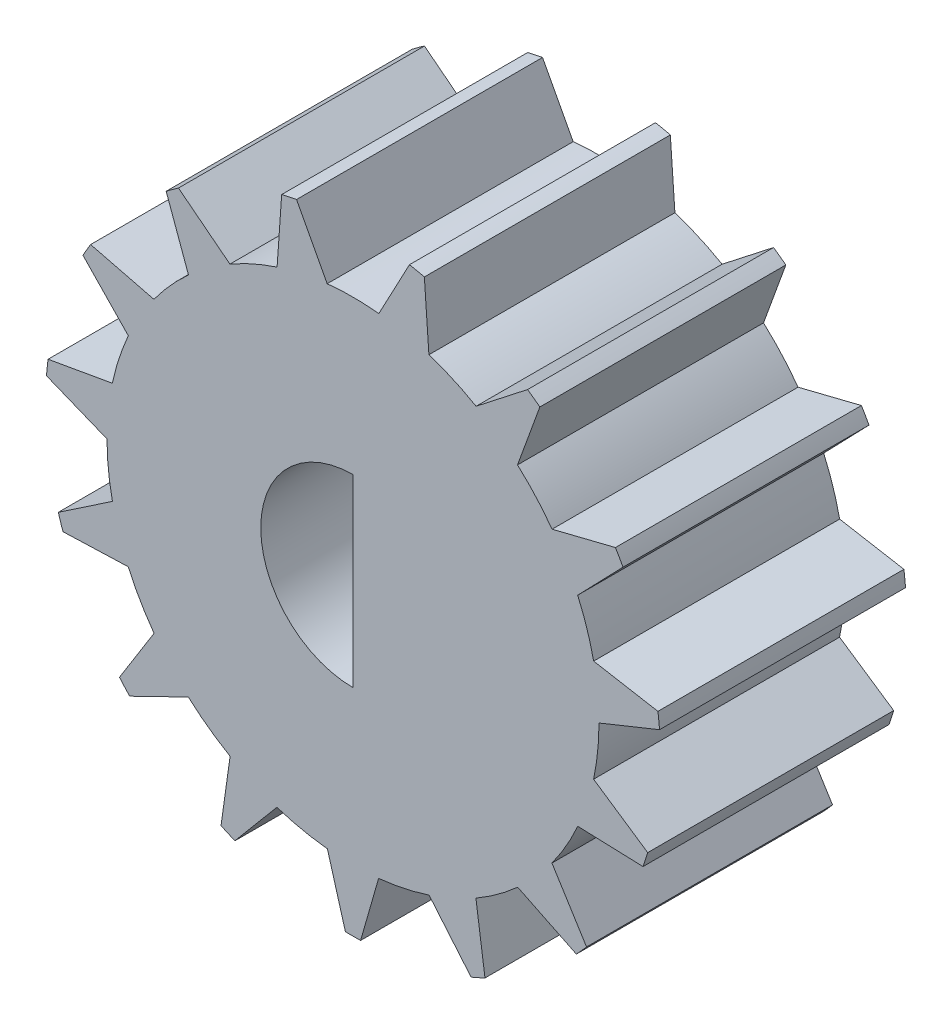
SolidWorks part; units mm, degrees
ref_plane "Front Plane" through (0, 0, 0) normal (0, 0, 1) x (1, 0, 0)
ref_plane "Top Plane" through (0, 0, 0) normal (0, 1, 0) x (1, 0, 0)
ref_plane "Right Plane" through (0, 0, 0) normal (1, 0, 0) x (0, 0, -1)
sketch "Sketch1" plane through (0, 0, 0) normal (0, 0, 1) x (1, 0, 0)
  line L0 (0, 0.75) -> (0, -0.75)
  circle A0 centre (0, 0) radius 2.5
  arc A1 (0, 0.75) -> (0, -0.75) centre (0, 0) ccw
  dimension "D1" = 5
  dimension "D2" = 1.5
extrude "Boss-Extrude1" add sketch "Sketch1" along normal blind 2
sketch "Sketch2" plane through (0, 0, 2) normal (0, 0, 1) x (1, 0, 0)
  line L0 (0, 0.5888) -> (0, 3.7281) construction
  line L1 (0, -0.75) -> (0, 0.75) construction
  line L2 (-0.21, 1.9889) -> (-0.466, 2.4705)
  line L3 (0.21, 1.9889) -> (0.466, 2.4705)
  circle A2 centre (0, 0) radius 2
  circle A3 centre (0, 0) radius 2.5141
  point P1 (0, 0)
  dimension "D1" = 4
  dimension "D2" = 28
  dimension "D3" = 0.466
  dimension "D4" = 0.21
extrude "Cut-Extrude2" cut sketch "Sketch2" against normal blind 2 contours A2 L0 A3 L2 | L0 A2 L3 A3
pattern_circular "CirPattern2" count 15 over 360 about axis through (0, 0, 0) along (0, 0, 1) of "Cut-Extrude2"
